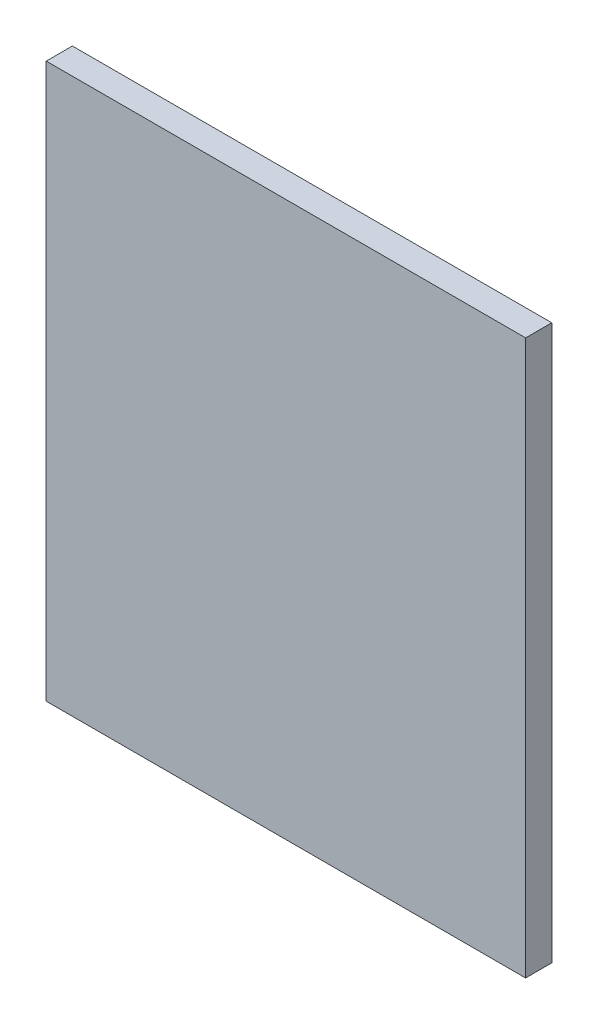
SolidWorks part; units mm, degrees
ref_plane "Plan de face" through (0, 0, 0) normal (0, 0, 1) x (1, 0, 0)
ref_plane "Plan de dessus" through (0, 0, 0) normal (0, 1, 0) x (1, 0, 0)
ref_plane "Plan de droite" through (0, 0, 0) normal (1, 0, 0) x (0, 0, -1)
sketch "Esquisse1" plane through (0, 0, 0) normal (0, 0, 1) x (1, 0, 0)
  line L1 (0, 0) -> (275, 0)
  line L2 (0, 0) -> (0, 318)
  line L3 (0, 318) -> (275, 318)
  line L4 (275, 0) -> (275, 318)
  dimension "D1" = 318
  dimension "D2" = 275
extrude "Boss.-Extru.1" add sketch "Esquisse1" along normal blind 15
